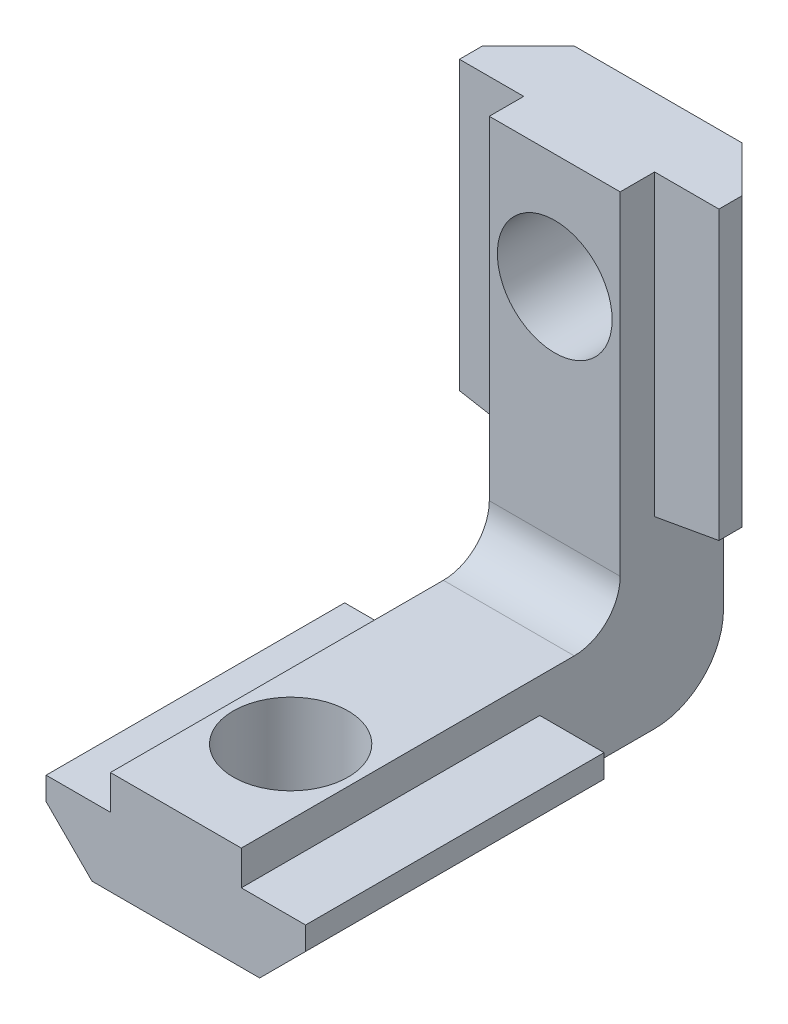
SolidWorks part; units mm, degrees
ref_plane "Front Plane" through (0, 0, 0) normal (0, 0, 1) x (1, 0, 0)
ref_plane "Top Plane" through (0, 0, 0) normal (0, 1, 0) x (1, 0, 0)
ref_plane "Right Plane" through (0, 0, 0) normal (1, 0, 0) x (0, 0, -1)
sketch "Sketch0" plane through (0, 0, 0) normal (1, 0, 0) x (0, 0, -1)
  line L0 (-21, 0) -> (0, 0) construction
  line L1 (0, 0) -> (0, 21) construction
  dimension "D1" = 21
  dimension "D2" = 21
ref_plane "Plane1" through (0, 0, 21) normal (0, 0, 1) x (1, 0, 0)
sketch "Sketch1" plane through (0, 0, 21) normal (0, 0, 1) x (1, 0, 0)
  line L0 (0, 4.5) -> (0, 0) construction
  line L2 (-2.85, 4.5) -> (2.85, 4.5)
  line L3 (-3.65, 0) -> (3.65, 0)
  line L4 (-3.65, 0) -> (-5.65, 2)
  line L5 (-5.65, 2) -> (-5.65, 3)
  line L6 (-5.65, 3) -> (-2.85, 3)
  line L7 (-2.85, 3) -> (-2.85, 4.5)
  line L8 (2.85, 3) -> (2.85, 4.5)
  line L9 (5.65, 3) -> (2.85, 3)
  line L10 (5.65, 2) -> (5.65, 3)
  line L11 (3.65, 0) -> (5.65, 2)
  dimension "D3" = 1
  dimension "D1" = 11.3
  dimension "D2" = 3
  dimension "D4" = 5.7
  dimension "D5" = 4.5
  dimension "D7" = 45
extrude "Boss-Extrude1" add sketch "Sketch1" against normal blind 13
sketch "Sketch2" plane through (0, 4.5, 0) normal (0, 1, 0) x (1, 0, 0)
  line L0 (0, -21) -> (0, 0) construction
  circle A0 centre (0, -16) radius 2.5
  dimension "D1" = 5
  dimension "D2" = 5
extrude "Cut-Extrude1" cut sketch "Sketch2" against normal through all
ref_plane "Plane2" through (0, 21, 0) normal (0, 1, 0) x (-1, 0, 0)
sketch "Sketch3" plane through (0, 21, 0) normal (0, 1, 0) x (-1, 0, 0)
  line L0 (2.85, 4.5) -> (-2.85, 4.5)
  line L1 (0, 4.5) -> (0, 0) construction
  line L2 (2.85, 4.5) -> (2.85, 3)
  line L3 (2.85, 3) -> (5.65, 3)
  line L4 (5.65, 3) -> (5.65, 2)
  line L5 (5.65, 2) -> (3.65, 0)
  line L6 (3.65, 0) -> (-3.65, 0)
  line L7 (-5.65, 2) -> (-3.65, 0)
  line L8 (-5.65, 3) -> (-5.65, 2)
  line L9 (-2.85, 3) -> (-5.65, 3)
  line L10 (-2.85, 4.5) -> (-2.85, 3)
  dimension "D1" = 11.3
  dimension "D2" = 5.7
  dimension "D3" = 4.5
  dimension "D4" = 3
  dimension "D5" = 1
  dimension "D6" = 45
extrude "Boss-Extrude2" add sketch "Sketch3" against normal blind 13 separate body
sketch "Sketch6" plane through (0, 0, 4.5) normal (0, 0, 1) x (1, 0, 0)
  line L0 (-5.65, 8) -> (-5.65, 8.5)
  line L1 (-5.65, 8) -> (-5.65, 21) construction
  line L2 (-5.65, 8.5) -> (-2.85, 8)
  line L3 (-2.85, 8) -> (-5.65, 8)
  line L4 (0, 0) -> (0, 8) construction
  line L5 (-2.85, 8) -> (2.85, 8) construction
  line L6 (2.85, 8) -> (5.65, 8)
  line L7 (5.65, 8.5) -> (2.85, 8)
  line L8 (5.65, 8) -> (5.65, 8.5)
  dimension "D1" = 0.5
extrude "Cut-Extrude2" cut sketch "Sketch6" against normal through all
sketch "Sketch7" plane through (0, 0, 0) normal (1, 0, 0) x (0, 0, -1)
  line L0 (-8, 0) -> (-3, 0)
  line L1 (0, 3) -> (0, 8)
  line L2 (-8, 4.5) -> (-6.5, 4.5)
  line L3 (-4.5, 6.5) -> (-4.5, 8)
  line L5 (0, 8) -> (-4.5, 8)
  line L6 (-8, 4.5) -> (-8, 0)
  arc A0 (-3, 0) -> (0, 3) centre (-3, 3) ccw
  arc A1 (-6.5, 4.5) -> (-4.5, 6.5) centre (-6.5, 6.5) ccw
  dimension "D1" = 3
  dimension "D2" = 2
extrude "Boss-Extrude3" add sketch "Sketch7" along normal up to vertex (2.85 mm away) and the other way up to vertex (2.85 mm away) up to point (2.85, 4.5, 8) other way up to point (-2.85, 4.5, 8)
sketch "Sketch5" plane through (0, 0, 0) normal (1, 0, 0) x (0, 0, -1)
  line L0 (-6.0634, 16) -> (1.8664, 16) construction
  line L1 (-4.5, 16) -> (0, 16)
  line L2 (-4.5, 16) -> (-4.5, 18.5)
  line L3 (0, 16) -> (0, 18.5)
  line L4 (-4.5, 18.5) -> (0, 18.5)
  line L5 (-4.5, 13.5) -> (0, 13.5) construction
  line L6 (0, 8.1429) -> (0, 21) construction
  line L8 (0, 21) -> (0, 16) construction
  line L9 (-4.5, 21) -> (0, 21) construction
  line L10 (-4.5, 6.5) -> (-4.5, 21) construction
  dimension "D1" = 5
  dimension "D2" = 5
revolve "Cut-Revolve1" cut sketch "Sketch5" angle 360 about L0
